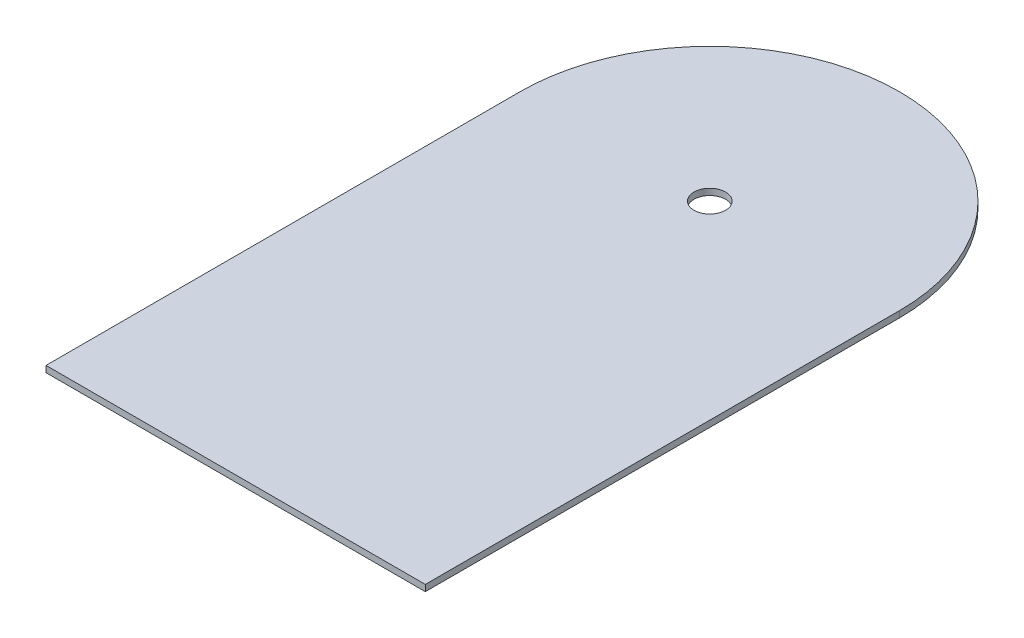
SolidWorks part; units mm, degrees
material "Lega 1060"
ref_plane "Piano frontale" through (0, 0, 0) normal (0, 0, 1) x (1, 0, 0)
ref_plane "Piano superiore" through (0, 0, 0) normal (0, 1, 0) x (1, 0, 0)
ref_plane "Piano destro" through (0, 0, 0) normal (1, 0, 0) x (0, 0, -1)
sketch "Schizzo1" plane through (0, 9.8206, 0) normal (0, 1, 0) x (1, 0, 0)
  line L0 (-30, 0) -> (-30, -75)
  line L1 (-30, -75) -> (30, -75)
  line L2 (30, -75) -> (30, 0)
  arc A0 (30, 0) -> (-30, 0) centre (0, 0) ccw
  circle A1 centre (0, 0) radius 2.5
  dimension "D1" = 30
  dimension "D2" = 75
extrude "Estrusione-Estrusione1" add sketch "Schizzo1" along normal blind 1
